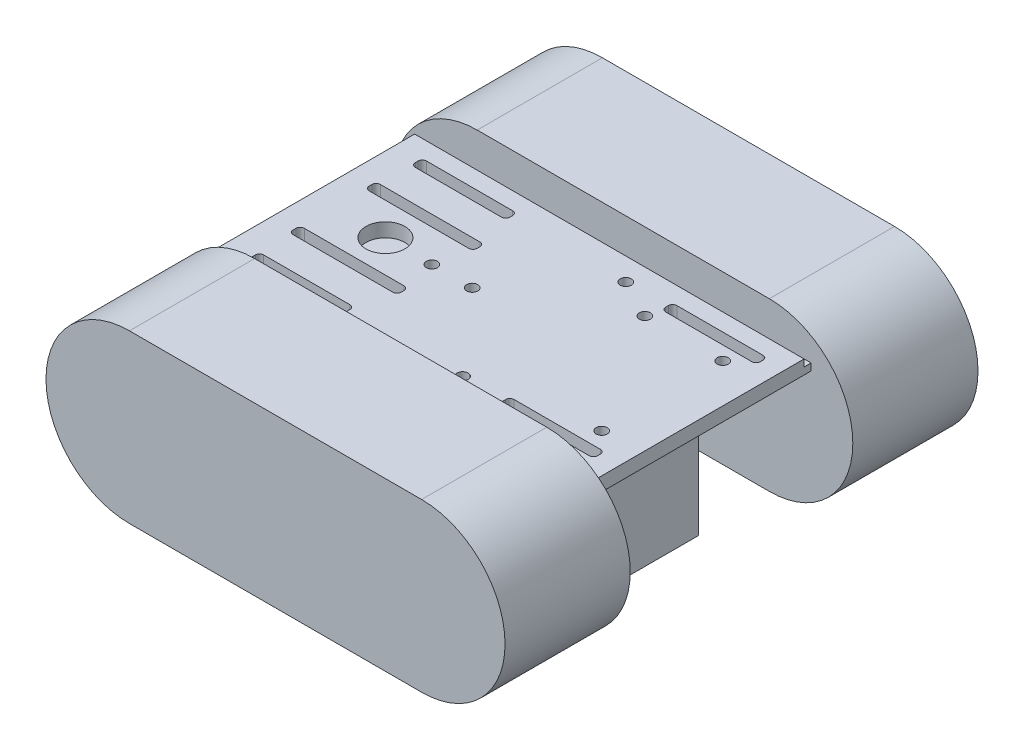
SolidWorks part; units mm, degrees
ref_plane "Plan de face" through (0, 0, 0) normal (0, 0, 1) x (1, 0, 0)
ref_plane "Plan de dessus" through (0, 0, 0) normal (0, 1, 0) x (1, 0, 0)
ref_plane "Plan de droite" through (0, 0, 0) normal (1, 0, 0) x (0, 0, -1)
sketch "Esquisse1" plane through (0, 0, 0) normal (0, 0, 1) x (1, 0, 0)
  line L0 (0, 30) -> (105, 30)
  line L1 (105, -30) -> (0, -30)
  arc A2 (0, 30) -> (0, -30) centre (0, 0) ccw
  arc A3 (105, -30) -> (105, 30) centre (105, 0) ccw
  dimension "D1" = 30
  dimension "D2" = 105
extrude "Boss.-Extru.1" add sketch "Esquisse1" along normal blind 170
sketch "Esquisse2" plane through (0, 30, 0) normal (0, 1, 0) x (1, 0, 0)
  line L0 (105, 0) -> (0, 0) construction
  line L1 (-60.8917, -45) -> (146.0328, -45)
  line L2 (-60.8917, -45) -> (-60.8917, -125)
  line L3 (-60.8917, -125) -> (146.0328, -125)
  line L4 (146.0328, -45) -> (146.0328, -125)
  dimension "D1" = 80
  dimension "D2" = 45
extrude "Enlèv. mat.-Extru.1" cut sketch "Esquisse2" against normal blind 170
sketch "Esquisse3" plane through (0, 0, 45) normal (0, 0, 1) x (1, 0, 0)
  line L0 (105, -30) -> (0, -30) construction
  line L1 (120, 17.5) -> (-20, 17.5)
  line L2 (120, 17.5) -> (120, 15)
  line L3 (120, 15) -> (-20, 15)
  line L4 (-20, 17.5) -> (-20, 15)
  arc A0 (0, 30) -> (0, -30) centre (0, 0) ccw construction
  dimension "D1" = 140
  dimension "D2" = 20
  dimension "D3" = 47.5
  dimension "D4" = 2.5
extrude "Boss.-Extru.2" add sketch "Esquisse3" along normal blind 80
sketch "Esquisse4" plane through (0, 17.5, 0) normal (0, 1, 0) x (1, 0, 0)
  line L0 (-20, -125) -> (-20, -45) construction
  line L1 (-20, -47.5) -> (120, -47.5)
  line L2 (-20, -47.5) -> (-20, -122.5)
  line L3 (-20, -122.5) -> (120, -122.5)
  line L4 (120, -47.5) -> (120, -122.5)
  line L5 (120, -125) -> (120, -45) construction
  line L6 (120, -125) -> (-20, -125) construction
  dimension "D1" = 75
  dimension "D2" = 2.5
extrude "Boss.-Extru.4" add sketch "Esquisse4" along normal blind 2.5
sketch "Esquisse5" plane through (0, 15, 0) normal (0, -1, 0) x (1, 0, 0)
  line L0 (-20, 45) -> (120, 45) construction
  line L1 (-17, 47.5) -> (16, 47.5)
  line L2 (-17, 47.5) -> (-17, 87.5)
  line L3 (-17, 87.5) -> (16, 87.5)
  line L4 (16, 47.5) -> (16, 87.5)
  line L5 (-20, 125) -> (-20, 45) construction
  line L6 (-20, 125) -> (120, 125) construction
  line L7 (117, 122.5) -> (84, 122.5)
  line L8 (117, 122.5) -> (117, 82.5)
  line L9 (117, 82.5) -> (84, 82.5)
  line L10 (84, 122.5) -> (84, 82.5)
  line L11 (120, 125) -> (120, 45) construction
  dimension "D1" = 33
  dimension "D2" = 2.5
  dimension "D3" = 40
  dimension "D4" = 3
  dimension "D5" = 2.5
  dimension "D6" = 40
  dimension "D7" = 33
  dimension "D8" = 3
extrude "Boss.-Extru.5" add sketch "Esquisse5" along normal blind 34
sketch "Esquisse6" plane through (0, 20, 0) normal (0, 1, 0) x (1, 0, 0)
  line L0 (-20, -47.5) -> (-20, -122.5) construction
  line L1 (-9.5, -53.75) -> (21.5, -53.75)
  line L2 (-11, -55.25) -> (-11, -56.25)
  line L3 (-9.5, -57.75) -> (21.5, -57.75)
  line L4 (23, -55.25) -> (23, -56.25)
  line L5 (-10.5, -69.35) -> (25.3, -69.35)
  line L6 (-12, -70.85) -> (-12, -71.85)
  line L7 (-10.5, -73.35) -> (25.3, -73.35)
  line L8 (26.8, -70.85) -> (26.8, -71.85)
  line L9 (-10.5, -96.65) -> (25.3, -96.65)
  line L10 (-12, -98.15) -> (-12, -99.15)
  line L11 (-10.5, -100.65) -> (25.3, -100.65)
  line L12 (26.8, -98.15) -> (26.8, -99.15)
  line L13 (-9.5, -112.25) -> (21.5, -112.25)
  line L14 (-11, -113.75) -> (-11, -114.75)
  line L15 (-9.5, -116.25) -> (21.5, -116.25)
  line L16 (23, -113.75) -> (23, -114.75)
  line L17 (120, -47.5) -> (-20, -47.5) construction
  line L20 (111.5, -53.75) -> (80.5, -53.75)
  line L21 (113, -55.25) -> (113, -56.25)
  line L22 (111.5, -57.75) -> (80.5, -57.75)
  line L23 (79, -55.25) -> (79, -56.25)
  line L24 (80.5, -116.25) -> (111.5, -116.25)
  line L25 (79, -114.75) -> (79, -113.75)
  line L26 (80.5, -112.25) -> (111.5, -112.25)
  line L27 (113, -114.75) -> (113, -113.75)
  line L28 (79, -55.75) -> (23, -55.25) construction
  line L29 (23, -114.25) -> (79, -114.25) construction
  line L30 (-20, -122.5) -> (120, -122.5) construction
  line L31 (120, -122.5) -> (120, -47.5) construction
  arc A0 (21.5, -112.25) -> (23, -113.75) centre (21.5, -113.75) cw
  arc A1 (23, -114.75) -> (21.5, -116.25) centre (21.5, -114.75) cw
  arc A2 (-9.5, -116.25) -> (-11, -114.75) centre (-9.5, -114.75) cw
  arc A3 (-9.5, -112.25) -> (-11, -113.75) centre (-9.5, -113.75) ccw
  arc A4 (26.8, -98.15) -> (25.3, -96.65) centre (25.3, -98.15) ccw
  arc A5 (26.8, -99.15) -> (25.3, -100.65) centre (25.3, -99.15) cw
  arc A6 (-12, -99.15) -> (-10.5, -100.65) centre (-10.5, -99.15) ccw
  arc A7 (-12, -98.15) -> (-10.5, -96.65) centre (-10.5, -98.15) cw
  arc A8 (-10.5, -73.35) -> (-12, -71.85) centre (-10.5, -71.85) cw
  arc A9 (-10.5, -69.35) -> (-12, -70.85) centre (-10.5, -70.85) ccw
  arc A10 (25.3, -73.35) -> (26.8, -71.85) centre (25.3, -71.85) ccw
  arc A11 (26.8, -70.85) -> (25.3, -69.35) centre (25.3, -70.85) ccw
  arc A12 (23, -55.25) -> (21.5, -53.75) centre (21.5, -55.25) ccw
  arc A13 (23, -56.25) -> (21.5, -57.75) centre (21.5, -56.25) cw
  arc A14 (-9.5, -57.75) -> (-11, -56.25) centre (-9.5, -56.25) cw
  arc A15 (-11, -55.25) -> (-9.5, -53.75) centre (-9.5, -55.25) cw
  arc A16 (111.5, -112.25) -> (113, -113.75) centre (111.5, -113.75) cw
  arc A17 (113, -114.75) -> (111.5, -116.25) centre (111.5, -114.75) cw
  arc A18 (79, -114.75) -> (80.5, -116.25) centre (80.5, -114.75) ccw
  arc A19 (79, -113.75) -> (80.5, -112.25) centre (80.5, -113.75) cw
  arc A20 (113, -56.25) -> (111.5, -57.75) centre (111.5, -56.25) cw
  arc A21 (79, -55.25) -> (80.5, -53.75) centre (80.5, -55.25) cw
  arc A22 (79, -56.25) -> (80.5, -57.75) centre (80.5, -56.25) ccw
  arc A23 (111.5, -53.75) -> (113, -55.25) centre (111.5, -55.25) cw
  circle A24 centre (7, -85) radius 7
  circle A25 centre (23.7, -85) radius 2
  circle A26 centre (38.2, -85) radius 2
  circle A27 centre (64, -114.25) radius 2
  circle A28 centre (64, -55.6161) radius 2
  circle A29 centre (78, -62.75) radius 2
  circle A30 centre (106, -62.75) radius 2
  circle A31 centre (106, -106.25) radius 2
  point P33 (23, -112.25)
  point P38 (-11, -116.25)
  point P41 (-11, -112.25)
  point P46 (26.8, -100.65)
  point P49 (-12, -100.65)
  point P52 (-12, -96.65)
  point P55 (-12, -73.35)
  point P58 (-12, -69.35)
  point P63 (26.8, -69.35)
  point P66 (23, -53.75)
  point P71 (-11, -57.75)
  point P74 (-11, -53.75)
  point P77 (113, -112.25)
  point P80 (113, -116.25)
  point P85 (79, -112.25)
  point P88 (113, -57.75)
  point P91 (79, -53.75)
  point P96 (113, -53.75)
  point P117 (120, -65.2497)
  dimension "D24" = 1.5
  dimension "D25" = 14
  dimension "D26" = 27
  dimension "D28" = 4
  dimension "D30" = 11.65
  dimension "D31" = 4
  dimension "D34" = 4
  dimension "D35" = 4
  dimension "D38" = 4
  dimension "D39" = 4
  dimension "D40" = 4
  dimension "D42" = 5
  dimension "D43" = 5
  dimension "D46" = 14
  dimension "D1" = 4
  dimension "D2" = 4
  dimension "D3" = 4
  dimension "D4" = 4
  dimension "D5" = 34
  dimension "D6" = 34
  dimension "D7" = 38.8
  dimension "D8" = 38.8
  dimension "D9" = 9
  dimension "D10" = 9
  dimension "D11" = 8
  dimension "D12" = 8
  dimension "D13" = 11.6
  dimension "D14" = 11.6
  dimension "D15" = 23.3
  dimension "D16" = 4
  dimension "6.25" = 6.25
  dimension "D17" = 4
  dimension "D18" = 34
  dimension "D19" = 34
  dimension "D20" = 56
  dimension "D21" = 56
  dimension "D22" = 6.25
  dimension "D23" = 6.25
  dimension "D27" = 11.65
  dimension "D29" = 16.7
  dimension "D32" = 11.65
  dimension "D33" = 14.5
  dimension "D36" = 15
  dimension "D37" = 15
  dimension "D41" = 6
  dimension "D44" = 28
  dimension "D45" = 14
extrude "Enlèv. mat.-Extru.2" cut sketch "Esquisse6" against normal blind 5
